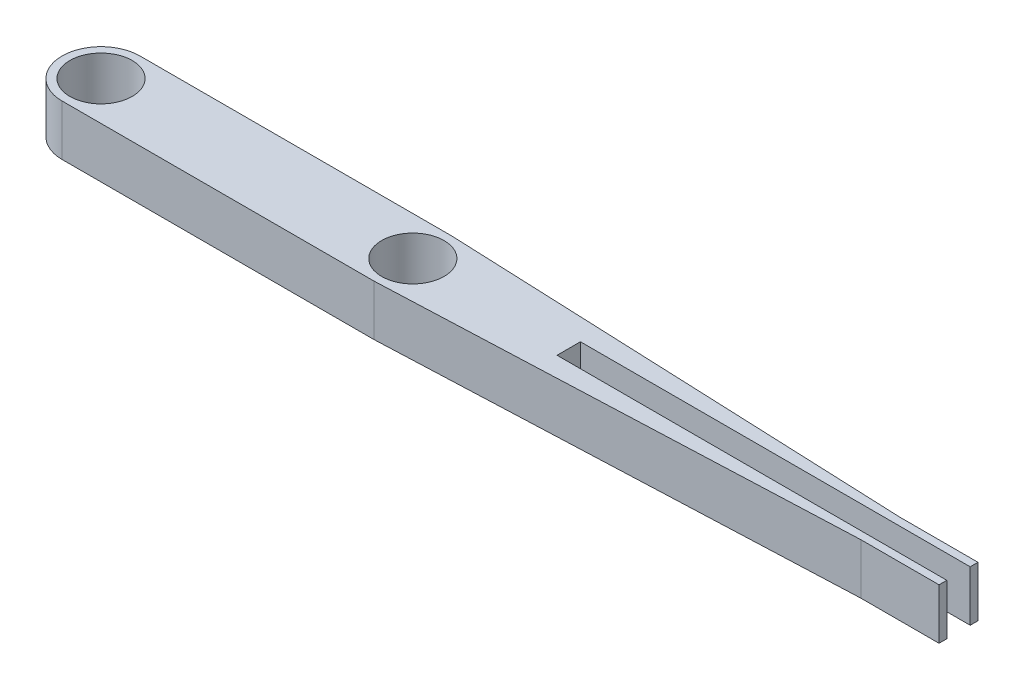
SolidWorks part; units mm, degrees
ref_plane "前视基准面" through (0, 0, 0) normal (0, 0, 1) x (1, 0, 0)
ref_plane "上视基准面" through (0, 0, 0) normal (0, 1, 0) x (1, 0, 0)
ref_plane "右视基准面" through (0, 0, 0) normal (1, 0, 0) x (0, 0, -1)
other "Configuration Table"
sketch "草图1" plane through (0, 0, 0) normal (0, 1, 0) x (1, 0, 0)
  line L0 (0, 0) -> (40, 0)
  line L1 (40, 0) -> (100, 0)
  line L2 (0, 5) -> (40, 5)
  line L3 (40, 5) -> (0, 5)
  line L4 (40, 5) -> (100, 2.5)
  line L5 (100, 0) -> (100, 2.5)
  line L6 (40, -5) -> (100, -2.5)
  line L7 (0, -5) -> (40, -5)
  line L8 (100, 0) -> (100, -2.5)
  circle A0 centre (0, 0) radius 4
  circle A1 centre (0, 0) radius 5
  circle A2 centre (40, 0) radius 4
  circle A3 centre (40, 0) radius 5
  point P11 (0, 0)
  dimension "D1" = 8
  dimension "D2" = 10
  dimension "D4" = 8
  dimension "D5" = 10
  dimension "D3" = 40
  dimension "D6" = 2.5
extrude "凸台-拉伸1" add sketch "草图1" along normal blind 6.5
sketch "草图2" plane through (0, 6.5, 0) normal (0, 1, 0) x (1, 0, 0)
  line L0 (100, 0) -> (80, 0)
  line L1 (100, -2.5) -> (100, 2.5) construction
  line L3 (60, -1.5) -> (100, -1.5)
  line L4 (60, -1.5) -> (60, 1.5)
  line L5 (60, 1.5) -> (100, 1.5)
  line L6 (100, -1.5) -> (100, 1.5)
  line L7 (80, 1.5) -> (80, -1.5) construction
  line L8 (60, 0) -> (100, 0) construction
  dimension "D1" = 20
  dimension "D2" = 3
extrude "切除-拉伸1" cut sketch "草图2" against normal through all contours L5 L6 L3 L4
sketch "草图3" plane through (100, 0, 0) normal (1, 0, 0) x (0, 0, -1)
  line L1 (-2.5, 6.5) -> (-1.5, 6.5)
  line L2 (-2.5, 6.5) -> (-2.5, 0)
  line L3 (-2.5, 0) -> (-1.5, 0)
  line L4 (-1.5, 6.5) -> (-1.5, 0)
  line L5 (-2.5, 6.5) -> (-1.5, 0) construction
  line L6 (-2.5, 0) -> (-1.5, 6.5) construction
  line L7 (1.5, 6.5) -> (2.5, 6.5)
  line L8 (1.5, 6.5) -> (1.5, 0)
  line L9 (1.5, 0) -> (2.5, 0)
  line L10 (2.5, 6.5) -> (2.5, 0)
  line L11 (1.5, 6.5) -> (2.5, 0) construction
  line L12 (1.5, 0) -> (2.5, 6.5) construction
  point P4 (-2, 3.25)
  point P11 (2, 3.25)
extrude "凸台-拉伸2" add sketch "草图3" along normal blind 10
